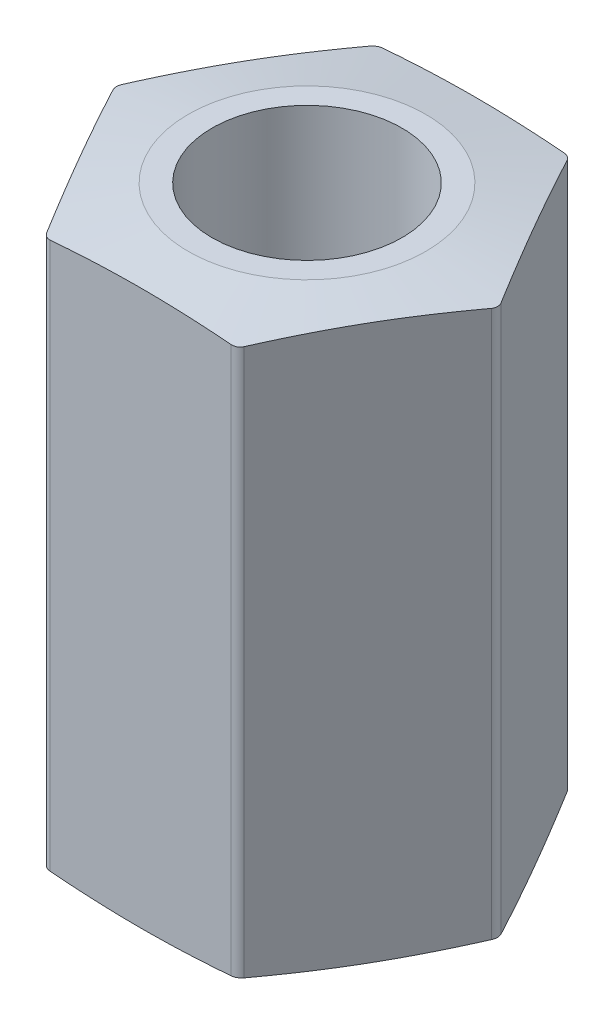
SolidWorks part; units mm, degrees
material "黄铜"
ref_plane "前视基准面" through (0, 0, 0) normal (0, 0, 1) x (1, 0, 0)
ref_plane "上视基准面" through (0, 0, 0) normal (0, 1, 0) x (1, 0, 0)
ref_plane "右视基准面" through (0, 0, 0) normal (1, 0, 0) x (0, 0, -1)
sketch "草图1" plane through (0, 0, 0) normal (0, 1, 0) x (1, 0, 0)
  line L1 (4.0415, 0) -> (2.0207, 3.5)
  line L2 (2.0207, 3.5) -> (-2.0207, 3.5)
  line L3 (-2.0207, 3.5) -> (-4.0415, 0)
  line L4 (-4.0415, 0) -> (-2.0207, -3.5)
  line L5 (-2.0207, -3.5) -> (2.0207, -3.5)
  line L6 (2.0207, -3.5) -> (4.0415, 0)
  circle A0 centre (0, 0) radius 3.5 construction
  dimension "六角对边距离" = 7
extrude "凸台-拉伸1" add sketch "草图1" along normal mid plane 12
fillet "圆角1" radius 0.2 6 edges at (2.0207, 0, -3.5) (-4.0415, 0, 0) (-2.0207, 0, -3.5) (-2.0207, 0, 3.5) (4.0415, 0, 0) (2.0207, 0, 3.5)
sketch "草图3" plane through (0, 6, 0) normal (0, 1, 0) x (1, 0, 0)
  circle A0 centre (0, 0) radius 2
  dimension "螺纹公称尺寸" = 4
extrude "切除-拉伸1" cut sketch "草图3" against normal blind 8
sketch "草图4" plane through (0, 0, 0) normal (0, 0, 1) x (1, 0, 0)
  line L0 (-2, 6) -> (-4.0105, 6) construction
  line L1 (-1.9053, 6) -> (1.9053, 6) construction
  line L2 (-4.0105, 6) -> (-4.0105, 5.75)
  line L4 (-4.0105, 6) -> (-4.0105, -6) construction
  line L5 (-2, 0.161) -> (-2, 8.9742) construction
  line L9 (-4.0105, 5.75) -> (-2.5, 6)
  line L10 (-2.5, 6) -> (-4.0105, 6)
  line L11 (0, 0) -> (0, 6) construction
  dimension "D1" = 0.25
  dimension "D2" = 0.5
revolve "切除-旋转1" cut sketch "草图4" angle 360 about L11
mirror "镜向1" about plane through (0, 0, 0) normal (0, 1, 0) of "切除-旋转1", "切除-拉伸1"
